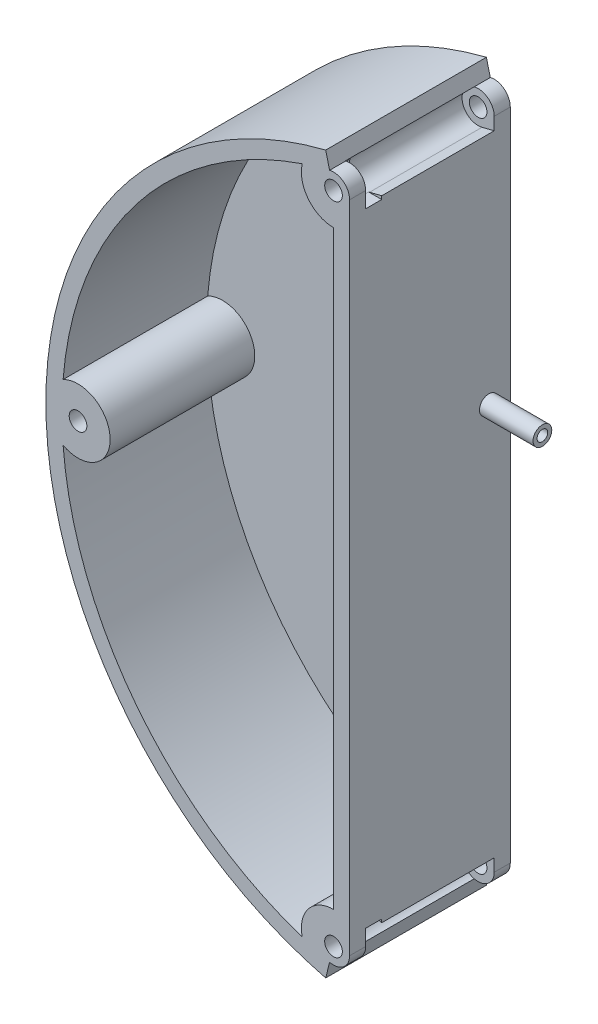
SolidWorks part; units mm, degrees
ref_plane "Front Plane" through (0, 0, 0) normal (0, 0, 1) x (1, 0, 0)
ref_plane "Top Plane" through (0, 0, 0) normal (0, 1, 0) x (1, 0, 0)
ref_plane "Right Plane" through (0, 0, 0) normal (1, 0, 0) x (0, 0, -1)
sketch "Sketch1" plane through (0, 0, 0) normal (0, 0, 1) x (1, 0, 0)
  line L0 (-12.3, -61.1139) -> (-12.3, 61.1139)
  line L1 (-12, -28.4) -> (-12, -52) construction
  line L2 (-16.7571, 66.9343) -> (-16.0286, 64.0241)
  line L4 (-16.7571, -66.9343) -> (-16.0286, -64.0241)
  line L5 (-63, 0) -> (0, 0) construction
  arc A1 (-16.0286, -64.0241) -> (-12.3, -61.1139) centre (-15.3, -61.1139) cw
  arc A3 (-16.0286, 64.0241) -> (-12.3, 61.1139) centre (-15.3, 61.1139) ccw
  circle A4 centre (-63, 0) radius 3
  arc A6 (-16.7571, 66.9343) -> (-16.7571, -66.9343) centre (0, 0) ccw
  dimension "D2" = 3
  dimension "D6" = 3
  dimension "D7" = 14.055
  dimension "D8" = 6
  dimension "D4" = 69
  dimension "D1" = 0.3
  dimension "D3" = 3
  dimension "D5" = 3
  dimension "D9" = 63
  dimension "D10" = 14.055
extrude "Boss-Extrude2" add sketch "Sketch1" along normal blind 30
shell "Shell1" thickness 3
sketch "Sketch3" plane through (-12.3, 0, 0) normal (1, 0, 0) x (0, 1, 0)
  line L0 (-61.1139, 0) -> (61.1139, 0) construction
  circle A0 centre (15, 4) radius 1.75
  dimension "D1" = 3.5
  dimension "D2" = 4
  dimension "D3" = 15
extrude "Boss-Extrude3" add sketch "Sketch3" along normal blind 10
sketch "Sketch5" plane through (0, 0, 0) normal (0, 0, 1) x (1, 0, 0)
  line L0 (-12.3, -61.1139) -> (-12.3, 61.1139)
  line L2 (-16.7571, 66.9343) -> (-16.0286, 64.0241)
  line L4 (-16.7571, -66.9343) -> (-16.0286, -64.0241)
  line L5 (-63, 0) -> (0, 0) construction
  circle A4 centre (-63, 0) radius 1.65
  circle A5 centre (-15.3, 61.1139) radius 1.65
  arc A6 (-16.7571, 66.9343) -> (-16.7571, -66.9343) centre (0, 0) ccw
  arc A7 (-16.0286, 64.0241) -> (-12.3, 61.1139) centre (-15.3, 61.1139) cw
  circle A8 centre (-15.3, -61.1139) radius 1.65
  arc A9 (-12.3, -61.1139) -> (-16.0286, -64.0241) centre (-15.3, -61.1139) cw
  dimension "D2" = 3.3
  dimension "D8" = 3.3
  dimension "D1" = 3.3
  dimension "D3" = 3
  dimension "D5" = 3
extrude "Boss-Extrude4" add sketch "Sketch5" along normal blind 3
sketch "Sketch6" plane through (0, 0, 30) normal (0, 0, 1) x (1, 0, 0)
  line L0 (-63, 3) -> (-68.9348, 3)
  line L1 (-63, -3) -> (-68.9348, -3)
  line L2 (-16.0286, -64.0241) -> (-14.5714, -58.2037) construction
  line L3 (-14.5714, -58.2037) -> (-12.3, -58.7724)
  line L4 (-12.3, -61.1139) -> (-12.3, 61.1139) construction
  line L5 (-12.3, -58.7724) -> (-12.3, -61.1139)
  line L6 (-16.0286, 64.0241) -> (-14.5714, 58.2037) construction
  line L7 (-14.5714, 58.2037) -> (-12.3, 58.7724)
  line L8 (-12.3, 58.7724) -> (-12.3, 61.1139)
  arc A1 (-63, -3) -> (-63, 3) centre (-63, 0) ccw
  arc A2 (-12.3, -61.1139) -> (-14.5714, -58.2037) centre (-15.3, -61.1139) ccw
  arc A3 (-14.5714, 58.2037) -> (-12.3, 61.1139) centre (-15.3, 61.1139) ccw
  arc A4 (-16.7571, 66.9343) -> (-16.7571, -66.9343) centre (0, 0) ccw construction
  arc A5 (-68.9348, 3) -> (-68.9348, -3) centre (-68.9348, 0) ccw
  arc A6 (-12.3, -61.1139) -> (-16.0286, -64.0241) centre (-15.3, -61.1139) ccw construction
  arc A7 (-16.0286, 64.0241) -> (-12.3, 61.1139) centre (-15.3, 61.1139) ccw construction
extrude "Cut-Extrude1" cut sketch "Sketch6" against normal up to surface (27 mm away) up to face at (-61.35, 0, 3)
sketch "Sketch7" plane through (0, 0, 30) normal (0, 0, 1) x (1, 0, 0)
  line L0 (-13.5968, -58.1639) -> (-11.8936, -58.1639)
  line L1 (-11.8936, -61.1139) -> (-13.5968, -58.1639) construction
  line L2 (-13.5968, -58.1639) -> (-17.0032, -58.1639)
  line L3 (-17.0032, -58.1639) -> (-18.7064, -61.1139)
  line L4 (-18.7064, -61.1139) -> (-17.0032, -64.0639)
  line L5 (-17.0032, -64.0639) -> (-13.5968, -64.0639)
  line L6 (-13.5968, -64.0639) -> (-11.8936, -61.1139)
  line L7 (-11.8936, 61.1139) -> (-13.5968, 64.0639)
  line L8 (-13.5968, 64.0639) -> (-17.0032, 64.0639)
  line L9 (-17.0032, 64.0639) -> (-18.7064, 61.1139)
  line L10 (-18.7064, 61.1139) -> (-17.0032, 58.1639)
  line L11 (-17.0032, 58.1639) -> (-13.5968, 58.1639)
  line L12 (-13.5968, 58.1639) -> (-11.8936, 61.1139) construction
  line L13 (-59.5936, 0) -> (-61.2968, 2.95)
  line L14 (-61.2968, 2.95) -> (-64.7032, 2.95)
  line L15 (-64.7032, 2.95) -> (-66.4064, 0)
  line L16 (-66.4064, 0) -> (-64.7032, -2.95)
  line L17 (-64.7032, -2.95) -> (-61.2968, -2.95)
  line L18 (-61.2968, -2.95) -> (-59.5936, 0)
  line L19 (-11.8936, -58.1639) -> (-11.8936, -61.1139)
  line L20 (-13.5968, 58.1639) -> (-11.8936, 58.1639)
  line L21 (-11.8936, 58.1639) -> (-11.8936, 61.1139)
  circle A0 centre (-15.3, -61.1139) radius 2.95 construction
  circle A1 centre (-15.3, 61.1139) radius 2.95 construction
  circle A2 centre (-63, 0) radius 2.95 construction
  dimension "D1" = 5.9
  dimension "D2" = 5.9
  dimension "D3" = 5.9
extrude "Cut-Extrude2" cut sketch "Sketch7" against normal blind 3 from offset 3 offset against normal yes
sketch "Sketch8" plane through (0, 0, 30) normal (0, 0, 1) x (1, 0, 0)
  line L0 (-63, 3) -> (-68.9348, 3)
  line L1 (-68.9348, 3) -> (-68.9348, -3)
  line L2 (-68.9348, -3) -> (-63, -3) construction
  line L3 (-63, -3) -> (-68.9348, -3) construction
  line L4 (-68.9348, -3) -> (-63, -3)
  line L5 (-12.3, -58.7724) -> (-14.5714, -58.2037)
  line L6 (-12.3, -58.7724) -> (-12.3, -61.1139)
  line L7 (-12.3, 61.1139) -> (-12.3, 58.7724)
  line L8 (-14.5714, 58.2037) -> (-12.3, 58.7724)
  circle A0 centre (-63, 0) radius 1.65
  arc A1 (-63, -3) -> (-63, 3) centre (-63, 0) ccw
  circle A2 centre (-15.3, -61.1139) radius 1.65
  arc A3 (-14.5714, -58.2037) -> (-12.3, -61.1139) centre (-15.3, -61.1139) ccw
  circle A4 centre (-15.3, 61.1139) radius 1.65
  arc A5 (-12.3, 61.1139) -> (-14.5714, 58.2037) centre (-15.3, 61.1139) ccw
extrude "Boss-Extrude5" add sketch "Sketch8" against normal blind 3
sketch "Sketch9" plane through (-2.3, 0, 0) normal (1, 0, 0) x (0, 1, 0)
  circle A0 centre (15, 4) radius 1
  dimension "D1" = 2
extrude "Cut-Extrude3" cut sketch "Sketch9" against normal blind 30
